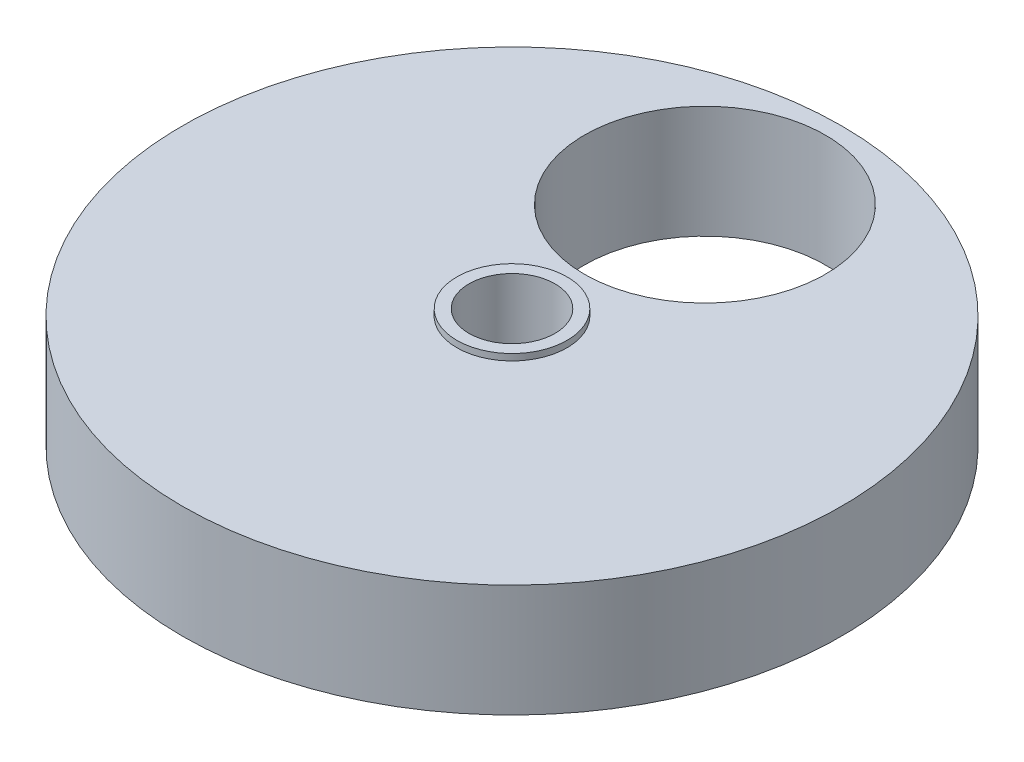
SolidWorks part; units mm, degrees
ref_plane "Front Plane" through (0, 0, 0) normal (0, 0, 1) x (1, 0, 0)
ref_plane "Top Plane" through (0, 0, 0) normal (0, 1, 0) x (1, 0, 0)
ref_plane "Right Plane" through (0, 0, 0) normal (1, 0, 0) x (0, 0, -1)
sketch "Sketch1" plane through (0, 0, 0) normal (0, 1, 0) x (1, 0, 0)
  circle A0 centre (0, 0) radius 20.5
  dimension "D1" = 41
extrude "Boss-Extrude1" add sketch "Sketch1" along normal blind 7
sketch "Sketch2" plane through (0, 7, 0) normal (0, 1, 0) x (1, 0, 0)
  circle A0 centre (0, 0) radius 2.675
  dimension "D1" = 5.35
extrude "Cut-Extrude1" cut sketch "Sketch2" against normal blind 7
sketch "Sketch3" plane through (0, 7, 0) normal (0, 1, 0) x (1, 0, 0)
  circle A0 centre (0, 0) radius 3.425
  circle A1 centre (0, 0) radius 2.675
  dimension "D1" = 5.35
  dimension "D2" = 6.85
extrude "Boss-Extrude2" add sketch "Sketch3" along normal blind 0.4
sketch "Sketch5" plane through (0, 7, 0) normal (0, 1, 0) x (1, 0, 0)
  circle A0 centre (0, 12) radius 7.5
  dimension "D1" = 15
  dimension "D2" = 12
extrude "Cut-Extrude3" cut sketch "Sketch5" against normal blind 7
